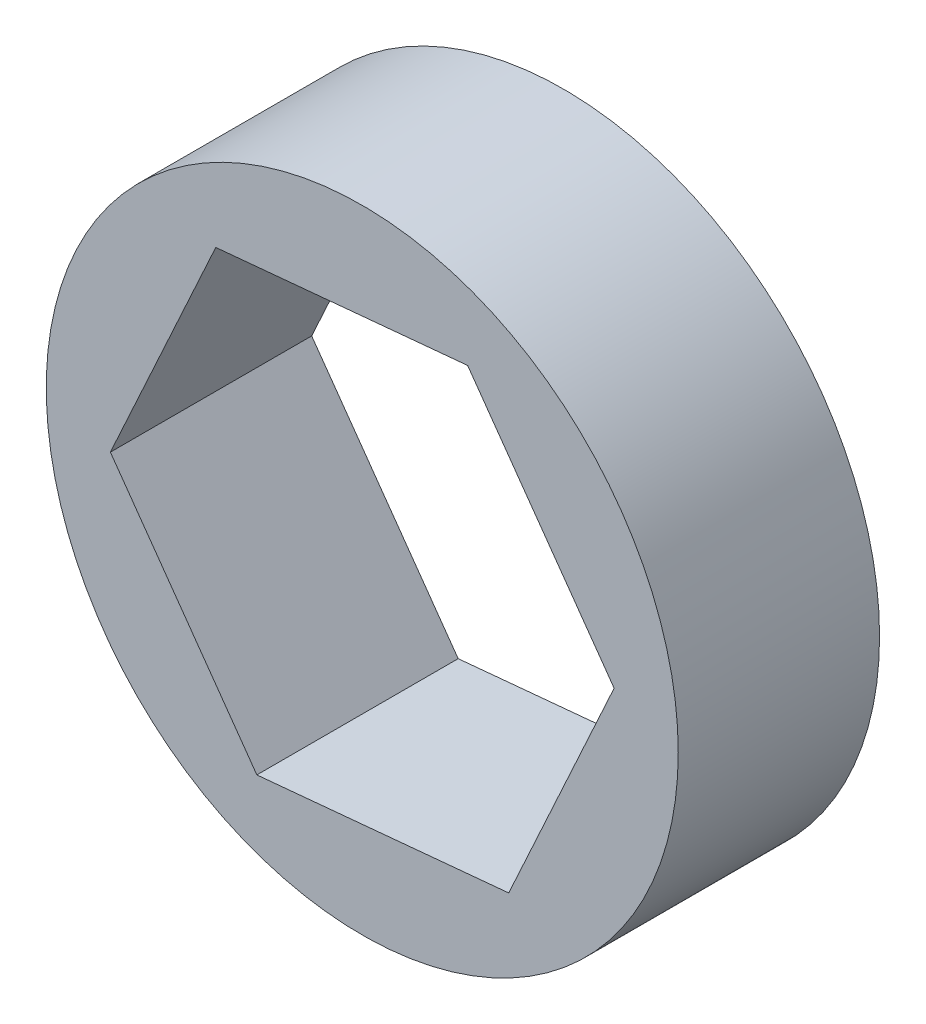
SolidWorks part; units mm, degrees
material "ABS"
ref_plane "Front Plane" through (0, 0, 0) normal (0, 0, 1) x (1, 0, 0)
ref_plane "Top Plane" through (0, 0, 0) normal (0, 1, 0) x (1, 0, 0)
ref_plane "Right Plane" through (0, 0, 0) normal (1, 0, 0) x (0, 0, -1)
sketch "Sketch1" plane through (0, 0, 0) normal (0, 0, 1) x (1, 0, 0)
  line L1 (-4.4153, 6.2174) -> (-7.592, -0.715)
  line L2 (-7.592, -0.715) -> (-3.1768, -6.9324)
  line L3 (-3.1768, -6.9324) -> (4.4153, -6.2174)
  line L4 (4.4153, -6.2174) -> (7.592, 0.715)
  line L5 (7.592, 0.715) -> (3.1768, 6.9324)
  line L6 (3.1768, 6.9324) -> (-4.4153, 6.2174)
  circle A0 centre (0, 0) radius 6.604 construction
  circle A1 centre (0, 0) radius 9.525
  dimension "D2" = 19.05
  dimension "D1" = 13.208
extrude "Boss-Extrude1" add sketch "Sketch1" along normal blind 6.0681
